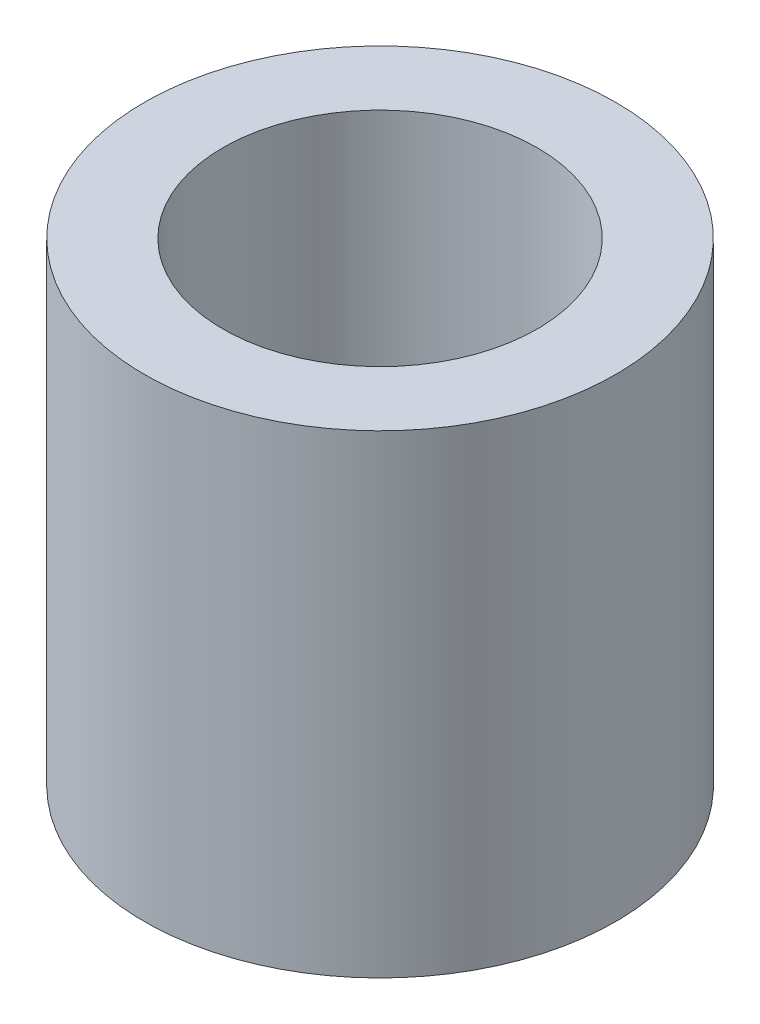
SolidWorks part; units mm, degrees
ref_plane "前视基准面" through (0, 0, 0) normal (0, 0, 1) x (1, 0, 0)
ref_plane "上视基准面" through (0, 0, 0) normal (0, 1, 0) x (1, 0, 0)
ref_plane "右视基准面" through (0, 0, 0) normal (1, 0, 0) x (0, 0, -1)
sketch "草图1" plane through (0, 0, 0) normal (0, 1, 0) x (1, 0, 0)
  circle A0 centre (0, 0) radius 2
  circle A1 centre (0, 0) radius 3
  dimension "D1" = 4
  dimension "D2" = 6
extrude "凸台-拉伸1" add sketch "草图1" along normal blind 6.0316
